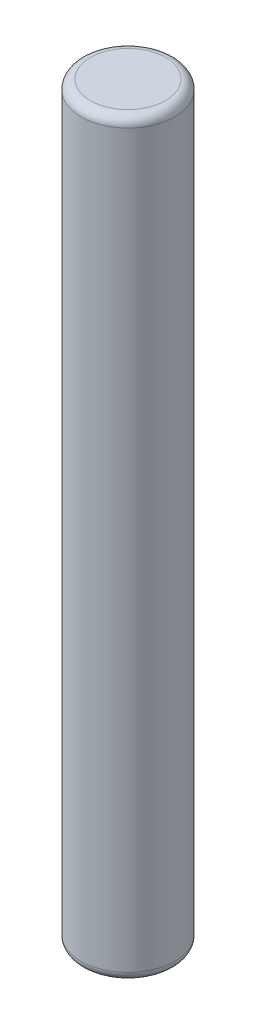
SolidWorks part; units mm, degrees
ref_plane "Front Plane" through (0, 0, 0) normal (0, 0, 1) x (1, 0, 0)
ref_plane "Top Plane" through (0, 0, 0) normal (0, 1, 0) x (1, 0, 0)
ref_plane "Right Plane" through (0, 0, 0) normal (1, 0, 0) x (0, 0, -1)
sketch "Sketch1" plane through (0, 0, 0) normal (0, 1, 0) x (1, 0, 0)
  circle A0 centre (0, 0) radius 2.5
  dimension "D1" = 5
extrude "Boss-Extrude1" add sketch "Sketch1" along normal blind 40
fillet "Fillet1" radius 0.5 2 edges at (0, 0, 2.5) (0, 40, 2.5)
